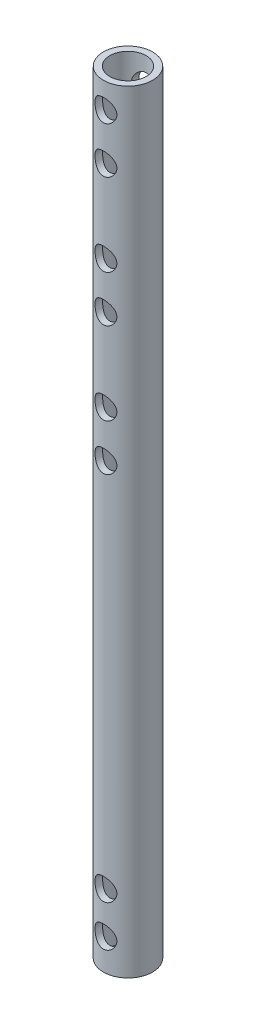
SolidWorks part; units mm, degrees
ref_plane "Front" through (0, 0, 0) normal (0, 0, 1) x (1, 0, 0)
ref_plane "Top" through (0, 0, 0) normal (0, 1, 0) x (1, 0, 0)
ref_plane "Right" through (0, 0, 0) normal (1, 0, 0) x (0, 0, -1)
ref_plane "25 cm" through (0, 250, 0) normal (0, 1, 0) x (1, 0, 0)
ref_plane "20 cm" through (0, 200, 0) normal (0, 1, 0) x (1, 0, 0)
sketch "Sketch1" plane through (0, 0, 0) normal (0, 1, 0) x (1, 0, 0)
  circle A0 centre (0, 0) radius 9.55
  circle A1 centre (0, 0) radius 7.05
  dimension "D1" = 19.1
  dimension "D2" = 2.5
extrude "Boss-Extrude1" add sketch "Sketch1" along normal blind 300
sketch "Sketch2" plane through (0, 0, 0) normal (0, 0, 1) x (1, 0, 0)
  line L0 (9.55, 300) -> (-9.55, 300) construction
  line L1 (9.55, 300) -> (-9.55, 300) construction
  line L2 (50, 250) -> (-50, 250) construction
  line L3 (50, 200) -> (-50, 200) construction
  circle A0 centre (0, 12) radius 4.25
  circle A1 centre (0, 28) radius 4.25
  circle A2 centre (0, 272) radius 4.25
  circle A3 centre (0, 290) radius 4.25
  circle A4 centre (0, 222) radius 4.25
  circle A5 centre (0, 240) radius 4.25
  circle A6 centre (0, 172) radius 4.25
  circle A7 centre (0, 190) radius 4.25
  point P2 (0, 0)
  point P6 (0, 0)
  point P11 (0, 0)
  point P12 (0, 138.2415)
  point P19 (0, 0)
  point P26 (0, 0)
  dimension "D1" = 8.5
  dimension "D2" = 12
  dimension "D4" = 8.5
  dimension "D7" = 8.5
  dimension "D10" = 8.5
  dimension "D3" = 16
  dimension "D5" = 18
  dimension "D6" = 10
  dimension "D8" = 18
  dimension "D9" = 10
  dimension "D11" = 18
  dimension "D12" = 10
extrude "Cut-Extrude1" cut sketch "Sketch2" against normal through all both and the other way through all
